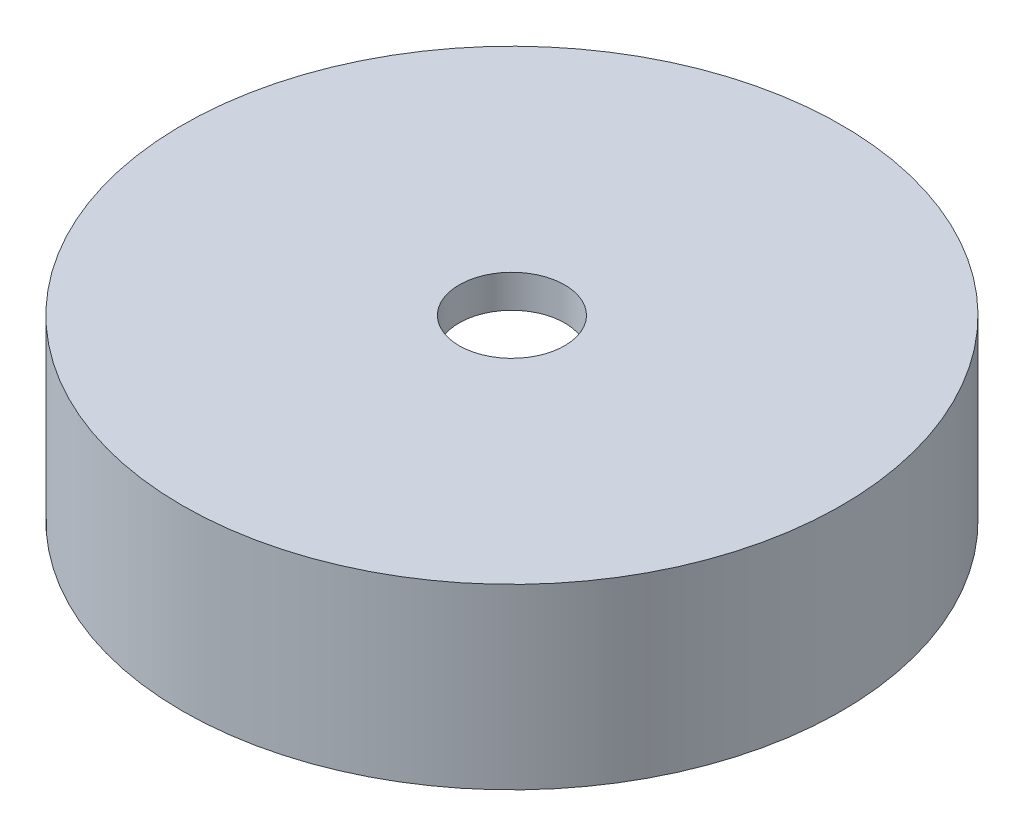
SolidWorks part; units mm, degrees
ref_plane "Front Plane" through (0, 0, 0) normal (0, 0, 1) x (1, 0, 0)
ref_plane "Top Plane" through (0, 0, 0) normal (0, 1, 0) x (1, 0, 0)
ref_plane "Right Plane" through (0, 0, 0) normal (1, 0, 0) x (0, 0, -1)
sketch "Sketch1" plane through (0, 0, 0) normal (0, 1, 0) x (1, 0, 0)
  circle A0 centre (0, 0) radius 45
  circle A1 centre (0, 0) radius 50
  dimension "D1" = 90
  dimension "D2" = 100
extrude "Boss-Extrude1" add sketch "Sketch1" along normal blind 22
sketch "Sketch2" plane through (0, 22, 0) normal (0, 1, 0) x (1, 0, 0)
  circle A0 centre (0, 0) radius 50 construction
  circle A1 centre (0, 0) radius 50
  circle A2 centre (0, 0) radius 2.5
  circle A3 centre (0, 0) radius 8
  circle M1 centre (0, 0) radius 50
  circle M2 centre (0, 0) radius 45
  dimension "D1" = 5
  dimension "D2" = 16
extrude "Boss-Extrude2" add sketch "Sketch2" along normal blind 5 contours A3 M2 | M1 M2
